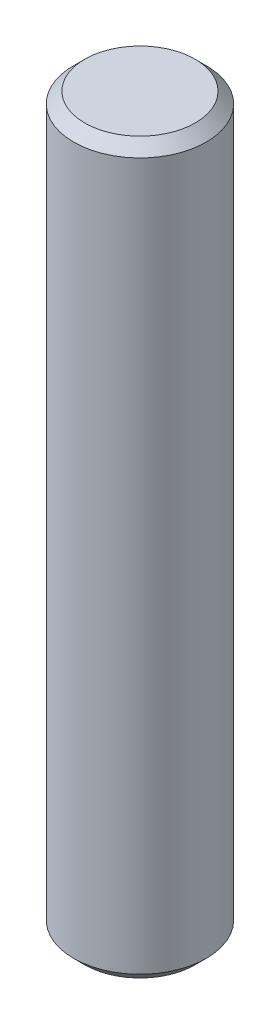
SolidWorks part; units mm, degrees
material "AISI 1045 Stal walcowana na zimno"
ref_plane "Płaszczyzna przednia" through (0, 0, 0) normal (0, 0, 1) x (1, 0, 0)
ref_plane "Płaszczyzna górna" through (0, 0, 0) normal (0, 1, 0) x (1, 0, 0)
ref_plane "Płaszczyzna prawa" through (0, 0, 0) normal (1, 0, 0) x (0, 0, -1)
sketch "Szkic1" plane through (0, 0, 0) normal (0, 1, 0) x (1, 0, 0)
  circle A0 centre (0, 0) radius 3
  dimension "D1" = 6
extrude "Dodanie-wyciągnięcie1" add sketch "Szkic1" along normal blind 33
chamfer "Sfazowanie1" distance 0.5 angle 45 2 edges at (0, 0, 3) (0, 33, 3)
